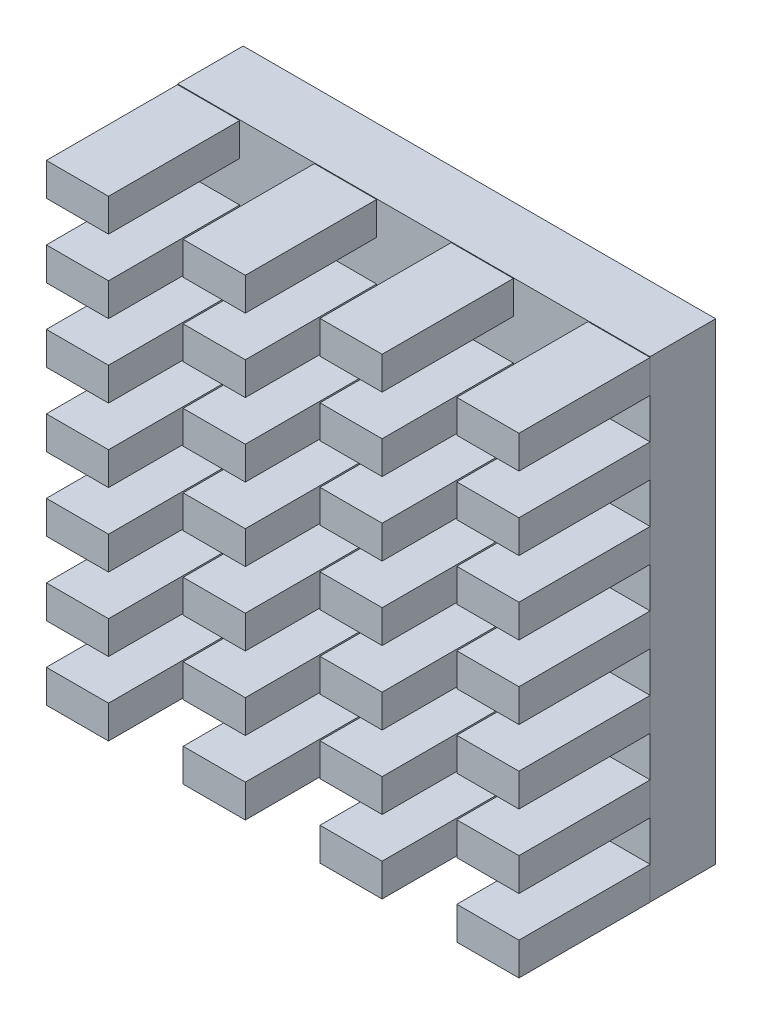
SolidWorks part; units mm, degrees
ref_plane "Alzado" through (0, 0, 0) normal (0, 0, 1) x (1, 0, 0)
ref_plane "Planta" through (0, 0, 0) normal (0, 1, 0) x (1, 0, 0)
ref_plane "Vista lateral" through (0, 0, 0) normal (1, 0, 0) x (0, 0, -1)
sketch "Croquis1" plane through (0, 0, 0) normal (0, 0, 1) x (1, 0, 0)
  line L1 (7.2, -7.2) -> (-7.2, -7.2)
  line L2 (7.2, -7.2) -> (7.2, 7.2)
  line L3 (7.2, 7.2) -> (-7.2, 7.2)
  line L4 (-7.2, -7.2) -> (-7.2, 7.2)
  line L5 (7.2, -7.2) -> (-7.2, 7.2) construction
  line L6 (7.2, 7.2) -> (-7.2, -7.2) construction
  point P0 (0, 0)
  dimension "D1" = 14.4
extrude "Saliente-Extruir1" add sketch "Croquis1" along normal blind 2
sketch "Croquis2" plane through (0, 0, 2) normal (0, 0, 1) x (1, 0, 0)
  line L0 (-3.03, -7.2) -> (-1.1357, -7.2)
  line L1 (-7.2, -7.2) -> (-5.3057, -7.2)
  line L2 (-7.2, -7.2) -> (-7.2, -6.2)
  line L3 (-7.2, -6.2) -> (-5.3057, -6.2)
  line L4 (-5.3057, -7.2) -> (-5.3057, -6.2)
  line L5 (-3.03, -7.2) -> (-3.03, -6.2)
  line L6 (-3.03, -6.2) -> (-1.1357, -6.2)
  line L7 (-1.1357, -7.2) -> (-1.1357, -6.2)
  line L8 (1.14, -7.2) -> (3.0343, -7.2)
  line L9 (1.14, -7.2) -> (1.14, -6.2)
  line L10 (1.14, -6.2) -> (3.0343, -6.2)
  line L11 (3.0343, -7.2) -> (3.0343, -6.2)
  line L12 (5.31, -7.2) -> (7.2043, -7.2)
  line L13 (5.31, -7.2) -> (5.31, -6.2)
  line L14 (5.31, -6.2) -> (7.2043, -6.2)
  line L15 (7.2043, -7.2) -> (7.2043, -6.2)
  line L16 (-3.03, -4.97) -> (-1.1357, -4.97)
  line L17 (-3.03, -4.97) -> (-3.03, -3.97)
  line L18 (-3.03, -3.97) -> (-1.1357, -3.97)
  line L19 (-1.1357, -4.97) -> (-1.1357, -3.97)
  line L20 (1.14, -4.97) -> (3.0343, -4.97)
  line L21 (1.14, -4.97) -> (1.14, -3.97)
  line L22 (1.14, -3.97) -> (3.0343, -3.97)
  line L23 (3.0343, -4.97) -> (3.0343, -3.97)
  line L24 (5.31, -4.97) -> (7.2043, -4.97)
  line L25 (5.31, -4.97) -> (5.31, -3.97)
  line L26 (5.31, -3.97) -> (7.2043, -3.97)
  line L27 (7.2043, -4.97) -> (7.2043, -3.97)
  line L28 (-3.03, -2.74) -> (-1.1357, -2.74)
  line L29 (-3.03, -2.74) -> (-3.03, -1.74)
  line L30 (-3.03, -1.74) -> (-1.1357, -1.74)
  line L31 (-1.1357, -2.74) -> (-1.1357, -1.74)
  line L32 (1.14, -2.74) -> (3.0343, -2.74)
  line L33 (1.14, -2.74) -> (1.14, -1.74)
  line L34 (1.14, -1.74) -> (3.0343, -1.74)
  line L35 (3.0343, -2.74) -> (3.0343, -1.74)
  line L36 (5.31, -2.74) -> (7.2043, -2.74)
  line L37 (5.31, -2.74) -> (5.31, -1.74)
  line L38 (5.31, -1.74) -> (7.2043, -1.74)
  line L39 (7.2043, -2.74) -> (7.2043, -1.74)
  line L40 (-3.03, -0.51) -> (-1.1357, -0.51)
  line L41 (-3.03, -0.51) -> (-3.03, 0.49)
  line L42 (-3.03, 0.49) -> (-1.1357, 0.49)
  line L43 (-1.1357, -0.51) -> (-1.1357, 0.49)
  line L44 (1.14, -0.51) -> (3.0343, -0.51)
  line L45 (1.14, -0.51) -> (1.14, 0.49)
  line L46 (1.14, 0.49) -> (3.0343, 0.49)
  line L47 (3.0343, -0.51) -> (3.0343, 0.49)
  line L48 (5.31, -0.51) -> (7.2043, -0.51)
  line L49 (5.31, -0.51) -> (5.31, 0.49)
  line L50 (5.31, 0.49) -> (7.2043, 0.49)
  line L51 (7.2043, -0.51) -> (7.2043, 0.49)
  line L52 (-3.03, 1.72) -> (-1.1357, 1.72)
  line L53 (-3.03, 1.72) -> (-3.03, 2.72)
  line L54 (-3.03, 2.72) -> (-1.1357, 2.72)
  line L55 (-1.1357, 1.72) -> (-1.1357, 2.72)
  line L56 (1.14, 1.72) -> (3.0343, 1.72)
  line L57 (1.14, 1.72) -> (1.14, 2.72)
  line L58 (1.14, 2.72) -> (3.0343, 2.72)
  line L59 (3.0343, 1.72) -> (3.0343, 2.72)
  line L60 (5.31, 1.72) -> (7.2043, 1.72)
  line L61 (5.31, 1.72) -> (5.31, 2.72)
  line L62 (5.31, 2.72) -> (7.2043, 2.72)
  line L63 (7.2043, 1.72) -> (7.2043, 2.72)
  line L64 (-3.03, 3.95) -> (-1.1357, 3.95)
  line L65 (-3.03, 3.95) -> (-3.03, 4.95)
  line L66 (-3.03, 4.95) -> (-1.1357, 4.95)
  line L67 (-1.1357, 3.95) -> (-1.1357, 4.95)
  line L68 (1.14, 3.95) -> (3.0343, 3.95)
  line L69 (1.14, 3.95) -> (1.14, 4.95)
  line L70 (1.14, 4.95) -> (3.0343, 4.95)
  line L71 (3.0343, 3.95) -> (3.0343, 4.95)
  line L72 (5.31, 3.95) -> (7.2043, 3.95)
  line L73 (5.31, 3.95) -> (5.31, 4.95)
  line L74 (5.31, 4.95) -> (7.2043, 4.95)
  line L75 (7.2043, 3.95) -> (7.2043, 4.95)
  line L76 (-3.03, 6.18) -> (-1.1357, 6.18)
  line L77 (-3.03, 6.18) -> (-3.03, 7.18)
  line L78 (-3.03, 7.18) -> (-1.1357, 7.18)
  line L79 (-1.1357, 6.18) -> (-1.1357, 7.18)
  line L80 (1.14, 6.18) -> (3.0343, 6.18)
  line L81 (1.14, 6.18) -> (1.14, 7.18)
  line L82 (1.14, 7.18) -> (3.0343, 7.18)
  line L83 (3.0343, 6.18) -> (3.0343, 7.18)
  line L84 (5.31, 6.18) -> (7.2043, 6.18)
  line L85 (5.31, 6.18) -> (5.31, 7.18)
  line L86 (5.31, 7.18) -> (7.2043, 7.18)
  line L87 (7.2043, 6.18) -> (7.2043, 7.18)
  line L88 (-7.2, -4.97) -> (-5.3057, -4.97)
  line L89 (-7.2, -4.97) -> (-7.2, -3.97)
  line L90 (-7.2, -3.97) -> (-5.3057, -3.97)
  line L91 (-5.3057, -4.97) -> (-5.3057, -3.97)
  line L92 (-7.2, -2.74) -> (-5.3057, -2.74)
  line L93 (-7.2, -2.74) -> (-7.2, -1.74)
  line L94 (-7.2, -1.74) -> (-5.3057, -1.74)
  line L95 (-5.3057, -2.74) -> (-5.3057, -1.74)
  line L96 (-7.2, -0.51) -> (-5.3057, -0.51)
  line L97 (-7.2, -0.51) -> (-7.2, 0.49)
  line L98 (-7.2, 0.49) -> (-5.3057, 0.49)
  line L99 (-5.3057, -0.51) -> (-5.3057, 0.49)
  line L100 (-7.2, 1.72) -> (-5.3057, 1.72)
  line L101 (-7.2, 1.72) -> (-7.2, 2.72)
  line L102 (-7.2, 2.72) -> (-5.3057, 2.72)
  line L103 (-5.3057, 1.72) -> (-5.3057, 2.72)
  line L104 (-7.2, 3.95) -> (-5.3057, 3.95)
  line L105 (-7.2, 3.95) -> (-7.2, 4.95)
  line L106 (-7.2, 4.95) -> (-5.3057, 4.95)
  line L107 (-5.3057, 3.95) -> (-5.3057, 4.95)
  line L108 (-7.2, 6.18) -> (-5.3057, 6.18)
  line L109 (-7.2, 6.18) -> (-7.2, 7.18)
  line L110 (-7.2, 7.18) -> (-5.3057, 7.18)
  line L111 (-5.3057, 6.18) -> (-5.3057, 7.18)
  point P5 (5.9632, 7.2)
  dimension "D1" = 1
  dimension "D2" = 1.8943
  dimension "D5" = 1.23
  dimension "D6" = 2.2757
  dimension "D4" = 4
  dimension "D3" = 7
extrude "Saliente-Extruir2" add sketch "Croquis2" along normal blind 4
